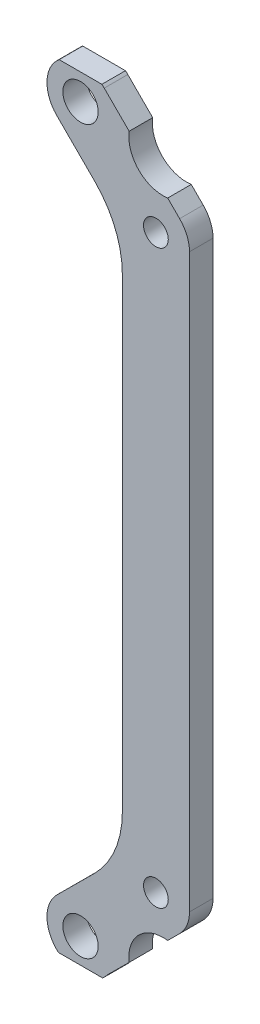
SolidWorks part; units mm, degrees
ref_plane "Спереди" through (0, 0, 0) normal (0, 0, 1) x (1, 0, 0)
ref_plane "Сверху" through (0, 0, 0) normal (0, 1, 0) x (1, 0, 0)
ref_plane "Справа" through (0, 0, 0) normal (1, 0, 0) x (0, 0, -1)
sketch "Skizze1" plane through (0, 0, 0) normal (0, 0, 1) x (1, 0, 0)
  circle A4 centre (43.5739, -31.0496) radius 1.05
  circle A5 centre (49.9739, -24.6496) radius 1.05
  circle A6 centre (49.9739, 23.8904) radius 1.05
  circle A7 centre (43.5739, 30.2904) radius 1.05
extrude "Linear-Austragen-Dünn1" add sketch "Skizze1" along normal blind 2 thin
sketch "Skizze3" plane through (0, 0, 0) normal (0, 0, -1) x (-1, 0, 0)
  line L0 (-47.9586, 21.8752) -> (-41.5624, 28.2715)
  line L1 (-51.9891, 25.9057) -> (-45.5891, 32.3057)
  line L2 (-45.5891, 32.3057) -> (-44.8842, 28.654)
  line L3 (-44.8842, 28.654) -> (-41.5624, 28.2715)
  line L4 (-47.9586, 21.8752) -> (-48.3536, 25.4642)
  line L5 (-48.3536, 25.4642) -> (-51.9891, 25.9057)
  line L6 (-52.8239, -24.6496) -> (-52.8239, 23.8904)
  line L7 (-52.8239, 23.8904) -> (-50.6096, 22.235)
  line L8 (-52.8239, -24.6496) -> (-50.1787, -22.8278)
  line L9 (-50.1787, -22.8278) -> (-47.1239, -24.6496)
  line L10 (-47.1239, -24.6496) -> (-47.1239, 22.7099)
  line L11 (-50.6096, 22.235) -> (-47.9586, 21.8752)
  line L12 (-51.9891, -26.6648) -> (-45.2648, -33.3437)
  line L13 (-41.5624, -29.0306) -> (-47.1239, -23.4897)
  line L14 (-51.9891, -26.6648) -> (-48.5933, -26.132)
  line L15 (-48.5933, -26.132) -> (-47.1239, -24.6496)
  line L16 (-45.2648, -33.3437) -> (-44.8842, -29.8084)
  line L17 (-44.8842, -29.8084) -> (-41.5624, -29.0306)
  circle A0 centre (-49.9739, 23.8904) radius 2.85 construction
  circle A1 centre (-43.5739, 30.2904) radius 2.85 construction
  circle A2 centre (-49.9739, -24.6496) radius 2.85 construction
  circle A3 centre (-43.5739, -31.0496) radius 2.85 construction
  circle M1 centre (-49.9739, 23.8904) radius 2.85
extrude "Aufsatz-Linear austragen1" add sketch "Skizze3" against normal blind 2 contours L16 L17 L13 L10 L15 L14 L12 | L9 L10 L0 L6 L8 M1 | L3 L2 L1 L0 M1
sketch "Skizze4" plane through (0, 0, 0) normal (0, 0, -1) x (-1, 0, 0)
  circle A0 centre (-50.5739, 29.7904) radius 2.9
  circle A1 centre (-50.5739, -30.5496) radius 2.9
  circle A2 centre (-43.5739, -31.0496) radius 1.05 construction
  circle A3 centre (-43.5739, 30.2904) radius 1.05 construction
  dimension "D1" = 0.5
  dimension "D2" = 7
  dimension "D3" = 5.8
  dimension "D4" = 7
  dimension "D5" = 0.5
extrude "Schnitt-Linear austragen1" cut sketch "Skizze4" against normal blind 2
sketch "Skizze7" plane through (0, 0, 2) normal (0, 0, 1) x (1, 0, 0)
  circle A0 centre (43.5739, -31.0496) radius 1.5
  circle A1 centre (43.5739, 30.2904) radius 1.5
  dimension "D1" = 3
extrude "Schnitt-Linear austragen3" cut sketch "Skizze7" against normal blind 4.5
fillet "Verrundung3" radius 8 1 edges at (47.1239, 22.7099, 1)
fillet "Verrundung4" radius 8 1 edges at (47.1239, -23.4897, 1)
sketch "Skizze8" plane through (0, 0, 0) normal (0, 0, -1) x (-1, 0, 0)
  line L1 (-47.1309, 34.884) -> (-38.7666, 34.884)
  line L2 (-47.1309, 34.884) -> (-47.1309, 32.488)
  line L3 (-47.1309, 32.488) -> (-38.7666, 32.488)
  line L4 (-38.7666, 34.884) -> (-38.7666, 32.488)
  line L5 (-48.0157, -36.2799) -> (-39.2684, -36.2799)
  line L6 (-48.0157, -36.2799) -> (-48.0157, -33.1953)
  line L7 (-48.0157, -33.1953) -> (-39.2684, -33.1953)
  line L8 (-39.2684, -36.2799) -> (-39.2684, -33.1953)
extrude "Schnitt-Linear austragen4" cut sketch "Skizze8" against normal blind 10
